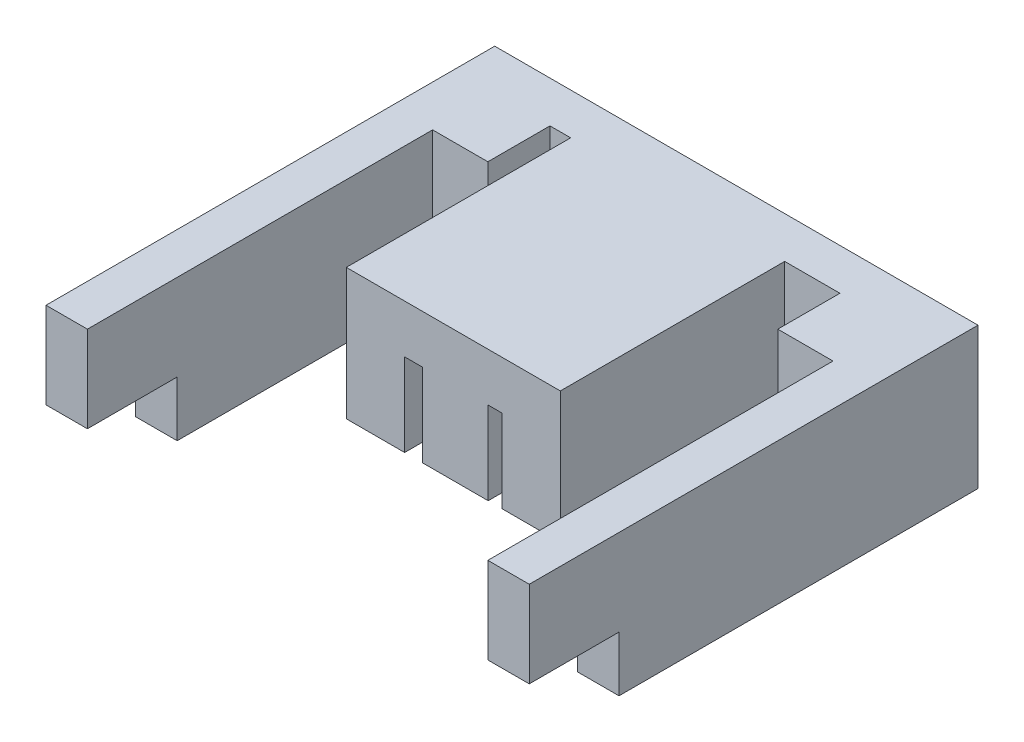
SolidWorks part; units mm, degrees
material "PBT General Purpose"
ref_plane "Front Plane" through (0, 0, 0) normal (0, 0, 1) x (1, 0, 0)
ref_plane "Top Plane" through (0, 0, 0) normal (0, 1, 0) x (1, 0, 0)
ref_plane "Right Plane" through (0, 0, 0) normal (1, 0, 0) x (0, 0, -1)
sketch "Sketch1" plane through (0, 0, 0) normal (0, 1, 0) x (1, 0, 0)
  line L0 (29, -32.5) -> (35, -32.5)
  line L1 (-35, 32.5) -> (35, 32.5)
  line L2 (-35, 32.5) -> (-35, -32.5)
  line L3 (-35, -32.5) -> (-29, -32.5)
  line L4 (35, 32.5) -> (35, -32.5)
  line L5 (-29, 26.5) -> (29, 26.5)
  line L6 (-29, 26.5) -> (-29, -32.5)
  line L8 (29, 26.5) -> (29, -32.5)
  point P8 (0, 26.5)
  point P10 (-35, 0)
  dimension "D1" = 70
  dimension "D2" = 65
  dimension "D3" = 6
  dimension "D4" = 6
  dimension "D5" = 6
extrude "Boss-Extrude1" add sketch "Sketch1" along normal blind 20.5
sketch "Sketch2" plane through (0, 0, 0) normal (0, -1, 0) x (1, 0, 0)
  line L0 (35, 32.5) -> (35, -32.5) construction
  line L1 (29, 32.5) -> (35, 32.5)
  line L2 (29, 32.5) -> (29, 19.5)
  line L3 (29, 19.5) -> (35, 19.5)
  line L4 (35, 32.5) -> (35, 19.5)
  line L5 (0, -1000) -> (0, 49000) construction
  line L6 (-29, -26.5) -> (29, -26.5) construction
  line L7 (-12.5, -26.5) -> (12.5, -26.5)
  line L8 (-12.5, -26.5) -> (-12.5, -32.5)
  line L9 (-12.5, -32.5) -> (12.5, -32.5)
  line L10 (12.5, -26.5) -> (12.5, -32.5)
  line L11 (35, -32.5) -> (-35, -32.5) construction
  line L12 (-29, 19.5) -> (-35, 19.5)
  line L13 (-35, 32.5) -> (-35, 19.5)
  line L14 (-29, 32.5) -> (-35, 32.5)
  line L15 (-29, 32.5) -> (-29, 19.5)
  point P18 (0, -26.5)
  point P19 (0, -26.5)
  dimension "D1" = 13
  dimension "D2" = 25
extrude "Cut-Extrude1" cut sketch "Sketch2" against normal blind 8
sketch "Sketch3" plane through (0, 20.5, 0) normal (0, 1, 0) x (1, 0, 0)
  line L0 (-29, -32.5) -> (-29, 26.5) construction
  line L1 (-14, 21) -> (9, 21)
  line L2 (-14, 21) -> (-14, -2)
  line L3 (-14, -2) -> (9, -2)
  line L4 (9, 21) -> (9, -2)
  line L5 (-29, 26.5) -> (29, 26.5) construction
  dimension "D1" = 23
  dimension "D2" = 23
  dimension "D3" = 15
  dimension "D4" = 5.5
extrude "Boss-Extrude2" add sketch "Sketch3" against normal offset from surface (7 mm away) 13.5 separate body up to face at (-25.5, 0, -13.1667)
sketch "Sketch4" plane through (0, 20.5, 0) normal (0, 1, 0) x (1, 0, 0)
  line L0 (-18, 26.5) -> (-18, -6)
  line L1 (-29, 26.5) -> (29, 26.5) construction
  line L2 (-18, -6) -> (13, -6)
  line L3 (13, -6) -> (13, 26.5)
  line L4 (-14, 21) -> (-14, -2)
  line L5 (-14, -2) -> (9, -2)
  line L6 (9, -2) -> (9, 21)
  line L7 (9, 21) -> (-14, 21)
  line L8 (-14, 21) -> (-14, -2)
  line L9 (-14, -2) -> (9, -2)
  line L10 (9, -2) -> (9, 21)
  line L11 (9, 21) -> (-14, 21)
  line L12 (13, 26.5) -> (-18, 26.5)
  line M12 (-29, 26.5) -> (29, 26.5)
  dimension "D2" = 4
  dimension "D3" = 4
  dimension "D4" = 4
  dimension "D1" = 0
extrude "Boss-Extrude4" add sketch "Sketch4" against normal offset from surface (19 mm away) 12 contours L2 L3 L0 L11 L10 L9 L8 M12
sketch "Sketch5" plane through (0, 1.5, 0) normal (0, -1, 0) x (1, 0, 0)
  line L0 (-14, -21) -> (9, -21) construction
  line L1 (-6.95, -21) -> (-9.55, -21)
  line L2 (-6.95, -21) -> (-6.95, -26.5)
  line L3 (-6.95, -26.5) -> (-9.55, -26.5)
  line L4 (-9.55, -21) -> (-9.55, -26.5)
  line L5 (12.5, -26.5) -> (-12.5, -26.5) construction
  line L6 (9, 2) -> (-14, 2) construction
  line L7 (-9.55, 2) -> (-6.95, 2)
  line L8 (-9.55, 2) -> (-9.55, 6)
  line L9 (-9.55, 6) -> (-6.95, 6)
  line L10 (-6.95, 2) -> (-6.95, 6)
  line L11 (13, 6) -> (-18, 6) construction
  line L12 (-18, 6) -> (-18, -26.5) construction
  line L13 (-18, 2) -> (-14, 2)
  line L14 (-18, 2) -> (-18, -13)
  line L15 (-18, -13) -> (-14, -13)
  line L16 (-14, 2) -> (-14, -13)
  line L17 (-14, 2) -> (-14, -21) construction
  line L18 (9, 2) -> (-14, 2) construction
  line L19 (2.55, 6) -> (4.55, 6)
  line L20 (2.55, 6) -> (2.55, 2)
  line L21 (2.55, 2) -> (4.55, 2)
  line L22 (4.55, 6) -> (4.55, 2)
  line L23 (-14, 2) -> (-14, -21) construction
  dimension "D1" = 2
  dimension "D2" = 9.5
  dimension "D3" = 15
  dimension "D4" = 2.6
  dimension "D5" = 4.45
extrude "Cut-Extrude2" cut sketch "Sketch5" against normal up to surface (12 mm away) up to face at (-2.5, 13.5, -9.5)
sketch "Sketch6" plane through (0, 0, 0) normal (0, -1, 0) x (1, 0, 0)
  line L1 (-35, 19.5) -> (-29, 19.5) construction
  line L2 (-29, -26.5) -> (-12.5, -26.5) construction
  circle A0 centre (-32, 14.5) radius 1.5
  circle A1 centre (-32, -21.5) radius 1.5
  point P6 (-32, 19.5)
  dimension "D1" = 3
  dimension "D3" = 3
  dimension "D2" = 5
  dimension "D4" = 5
extrude "Cut-Extrude3" cut sketch "Sketch6" against normal blind 10
mirror "Mirror1" about plane through (0, 0, 0) normal (1, 0, 0) of "Cut-Extrude3"
sketch "Sketch7" plane through (0, 20.5, 0) normal (0, 1, 0) x (1, 0, 0)
  line L1 (29, 26.5) -> (21, 26.5)
  line L2 (29, 26.5) -> (29, 17.5)
  line L3 (29, 17.5) -> (21, 17.5)
  line L4 (21, 26.5) -> (21, 17.5)
  line L5 (-29, 26.5) -> (-21, 26.5)
  line L6 (-29, 26.5) -> (-29, 17.5)
  line L7 (-29, 17.5) -> (-21, 17.5)
  line L8 (-21, 26.5) -> (-21, 17.5)
  dimension "D1" = 8
  dimension "D2" = 9
  dimension "D3" = 9
  dimension "D4" = 8
extrude "Boss-Extrude5" add sketch "Sketch7" against normal up to surface (20.5 mm away) up to face at (32, 0, 13)
sketch "Sketch8" plane through (0, 0, -32.5) normal (0, 0, -1) x (-1, 0, 0)
  line L0 (-35, 20.5) -> (-35, 0) construction
  line L1 (35, 20.5) -> (35, 0) construction
  line L2 (12.5, 0) -> (35, 0) construction
  line L3 (-35, 0) -> (-12.5, 0) construction
  circle A0 centre (-25, 11) radius 2
  circle A1 centre (25, 11) radius 2
  point P10 (26.9181, 7.8217)
  dimension "D1" = 4
  dimension "D2" = 4
  dimension "D5" = 11
  dimension "D6" = 11
  dimension "D3" = 10
  dimension "D4" = 10
extrude "Cut-Extrude4" cut sketch "Sketch8" against normal blind 10
equation "\"body_height\"= 41mm"
equation "\"D1@Boss-Extrude1\"=\"body_height\" / 2"
equation "\"D1@Boss-Extrude2\"=12+1.5"
